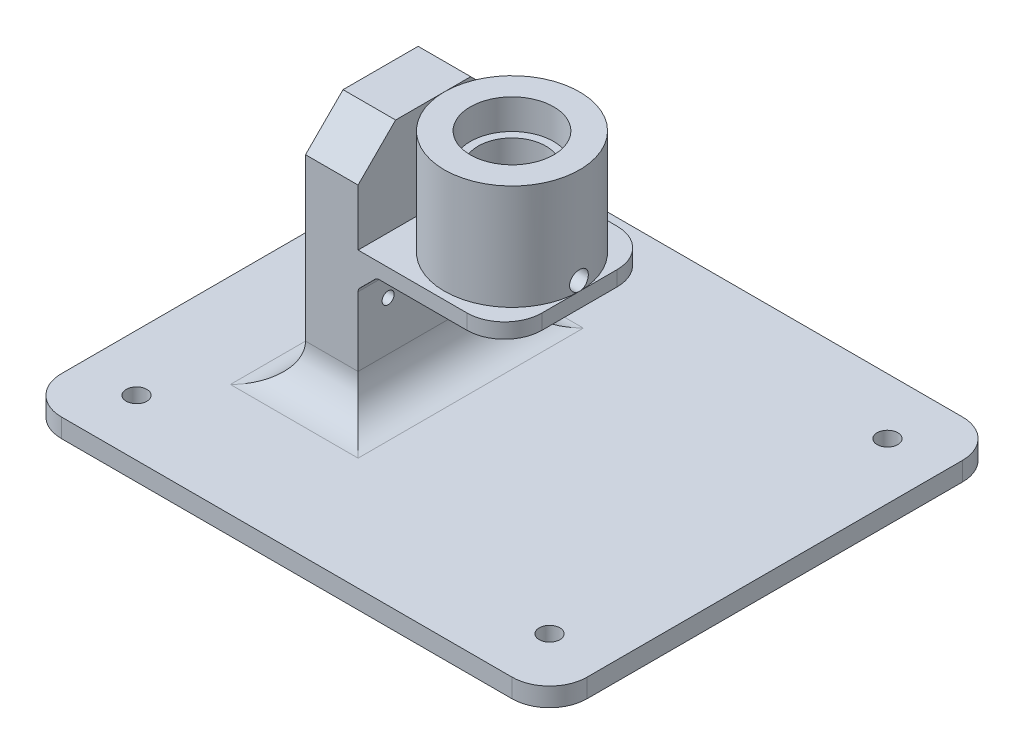
SolidWorks part; units mm, degrees
ref_plane "Front Plane" through (0, 0, 0) normal (0, 0, 1) x (1, 0, 0)
ref_plane "Top Plane" through (0, 0, 0) normal (0, 1, 0) x (1, 0, 0)
ref_plane "Right Plane" through (0, 0, 0) normal (1, 0, 0) x (0, 0, -1)
sketch "Bench_footprint_140x120_profile" plane through (0, 0, 0) normal (0, 1, 0) x (1, 0, 0)
  line L1 (-60, -60) -> (60, -60)
  line L2 (-70, -50) -> (-70, 50)
  line L3 (-60, 60) -> (60, 60)
  line L4 (70, -50) -> (70, 50)
  arc A0 (60, -60) -> (70, -50) centre (60, -50) ccw
  arc A1 (-60, -60) -> (-70, -50) centre (-60, -50) cw
  arc A2 (-70, 50) -> (-60, 60) centre (-60, 50) cw
  arc A3 (60, 60) -> (70, 50) centre (60, 50) cw
  point P4 (70, -60)
  point P10 (-70, -60)
  point P13 (-70, 60)
  point P16 (70, 60)
  dimension "D5" = 10
  dimension "D1" = 140
  dimension "D2" = 120
  dimension "D3" = 70
  dimension "D4" = 60
extrude "Bench_footprint_140x120" add sketch "Bench_footprint_140x120_profile" along normal blind 5
sketch "Backbone_profile" plane through (0, 0, 0) normal (0, 0, 1) x (1, 0, 0)
  line L1 (-35, 5) -> (-21, 5)
  line L2 (-35, 5) -> (-35, 68)
  line L3 (-35, 68) -> (-21, 68)
  line L4 (-21, 5) -> (-21, 68)
  dimension "D1" = 14
  dimension "D2" = 63
  dimension "D3" = 21
  dimension "D4" = 5
extrude "Backbone" add sketch "Backbone_profile" along normal blind 40 from offset 20 offset against normal yes
sketch "Removable_servo_mount_M3_profile" plane through (0, 0, 0) normal (1, 0, 0) x (0, 0, -1)
  circle A0 centre (12, 28) radius 1.6
  circle A1 centre (-12, 28) radius 1.6
  dimension "D1" = 3.2
  dimension "D2" = 3.2
  dimension "D3" = 12
  dimension "D4" = 12
  dimension "D5" = 28
extrude "Removable_servo_mount_M3" cut sketch "Removable_servo_mount_M3_profile" along normal through all from offset 40
sketch "Bearing_bridge_profile" plane through (0, 0, 0) normal (0, 1, 0) x (1, 0, 0)
  line L1 (-35, -20) -> (18, -20)
  line L2 (-35, -20) -> (-35, 20)
  line L3 (-35, 20) -> (18, 20)
  line L4 (18, -20) -> (18, 20)
  dimension "D1" = 53
  dimension "D2" = 40
  dimension "D3" = 18
  dimension "D4" = 20
extrude "Bearing_bridge" add sketch "Bearing_bridge_profile" along normal blind 4 from offset 39
sketch "Bridge_horn_clearance_profile" plane through (0, 0, 0) normal (0, 1, 0) x (1, 0, 0)
  circle A0 centre (0, 0) radius 14
  dimension "D1" = 28
extrude "Bridge_horn_clearance" cut sketch "Bridge_horn_clearance_profile" along normal through all from offset 38
sketch "Drive_collar_chamber_profile" plane through (0, 0, 0) normal (0, 1, 0) x (1, 0, 0)
  circle A0 centre (0, 0) radius 18
  circle A1 centre (0, 0) radius 14
  dimension "D1" = 36
  dimension "D2" = 28
extrude "Drive_collar_chamber" add sketch "Drive_collar_chamber_profile" along normal blind 5 from offset 43
sketch "Bearing_tower_profile" plane through (0, 0, 0) normal (0, 1, 0) x (1, 0, 0)
  circle A0 centre (0, 0) radius 18
  circle A1 centre (0, 0) radius 11.1
  dimension "D1" = 36
  dimension "D2" = 22.2
extrude "Bearing_tower" add sketch "Bearing_tower_profile" along normal blind 23 from offset 48
sketch "Bearing_separation_shoulder_profile" plane through (0, 0, 0) normal (0, 1, 0) x (1, 0, 0)
  circle A0 centre (0, 0) radius 11.1
  circle A1 centre (0, 0) radius 9
  dimension "D1" = 22.2
  dimension "D2" = 18
extrude "Bearing_separation_shoulder" add sketch "Bearing_separation_shoulder_profile" along normal blind 8 from offset 55
sketch "Bench_clamp_holes_profile" plane through (0, 0, 0) normal (0, 1, 0) x (1, 0, 0)
  circle A0 centre (-55, -45) radius 2.75
  circle A1 centre (55, -45) radius 2.75
  circle A2 centre (-55, 45) radius 2.75
  circle A3 centre (55, 45) radius 2.75
  dimension "D1" = 5.5
  dimension "D2" = 5.5
  dimension "D3" = 5.5
  dimension "D4" = 5.5
  dimension "D5" = 55
  dimension "D6" = 55
  dimension "D7" = 45
  dimension "D8" = 45
extrude "Bench_clamp_holes" cut sketch "Bench_clamp_holes_profile" along normal through all from offset 1
sketch "Yaw_crossbolt_access_profile" plane through (0, 0, 0) normal (1, 0, 0) x (0, 0, -1)
  circle A0 centre (0, 45.5) radius 2.5
  dimension "D1" = 5
  dimension "D2" = 45.5
extrude "Yaw_crossbolt_access" cut sketch "Yaw_crossbolt_access_profile" along normal through all from offset 40
fillet "Fillet2" radius 10 2 edges at (18, 41, -20) (18, 41, 20)
sketch "Sketch1" plane through (0, 0, 20) normal (0, 0, 1) x (1, 0, 0)
  line L0 (-21, 34) -> (-16, 39)
  line L1 (-21, 5) -> (-21, 39) construction
  line L2 (-21, 39) -> (8, 39) construction
  line L3 (-16, 39) -> (-21, 39)
  line L4 (-21, 39) -> (-21, 34)
  dimension "D1" = 45
  dimension "D2" = 5
extrude "Boss-Extrude1" add sketch "Sketch1" against normal up to surface (40 mm away) up to face at (-17.25, 38.75, -20)
fillet "Fillet6" radius 1.5 2 edges at (-21, 34, 0) (-16, 39, 0)
fillet "Fillet7" radius 10 4 edges at (-21, 5, 0) (-28, 5, -20) (-28, 5, 20) (-35, 5, 0)
chamfer "Chamfer1" distance 10 angle 45 2 edges at (-28, 68, -20) (-28, 68, 20)
